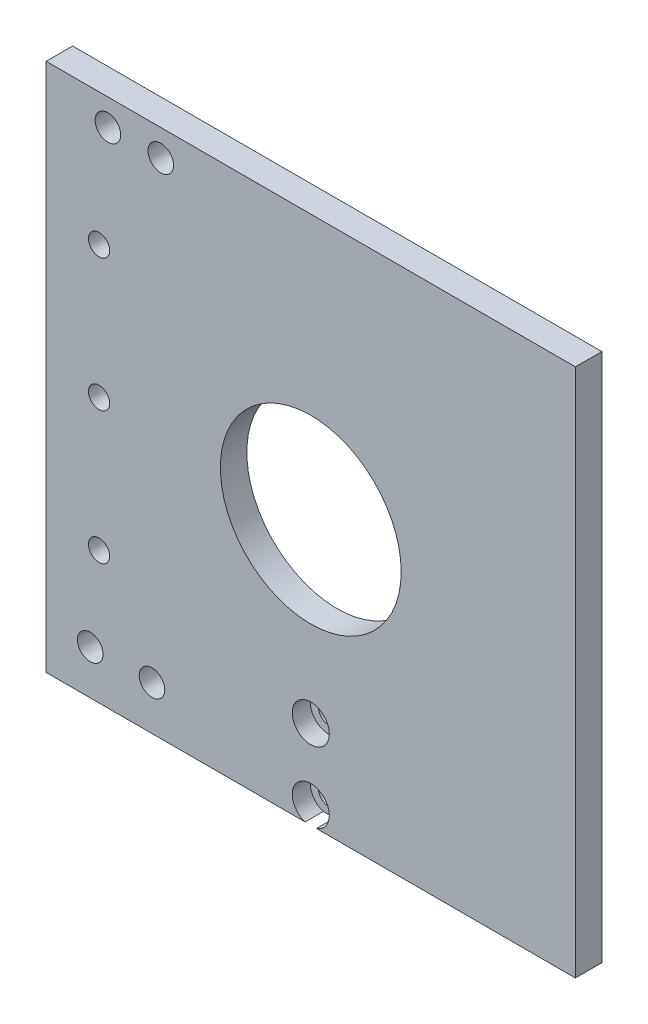
SolidWorks part; units mm, degrees
ref_plane "Front Plane" through (0, 0, 0) normal (0, 0, 1) x (1, 0, 0)
ref_plane "Top Plane" through (0, 0, 0) normal (0, 1, 0) x (1, 0, 0)
ref_plane "Right Plane" through (0, 0, 0) normal (1, 0, 0) x (0, 0, -1)
sketch "Sketch1" plane through (0, 0, 0) normal (0, 0, 1) x (1, 0, 0)
  line L1 (30, -30) -> (-30, -30)
  line L2 (30, -30) -> (30, 30)
  line L3 (30, 30) -> (-30, 30)
  line L4 (-30, -30) -> (-30, 30)
  line L5 (30, -30) -> (-30, 30) construction
  line L6 (30, 30) -> (-30, -30) construction
  point P0 (0, 0)
  dimension "D1" = 60
  dimension "D2" = 60
extrude "Boss-Extrude1" add sketch "Sketch1" along normal blind 3
sketch "Sketch2" plane through (0, 0, 3) normal (0, 0, 1) x (1, 0, 0)
  circle A0 centre (0, 0) radius 10.25
extrude "Cut-Extrude1" cut sketch "Sketch2" against normal through all
sketch "Sketch3" plane through (0, 0, 0) normal (0, 0, -1) x (-1, 0, 0)
  circle A0 centre (18, -25) radius 1.45
  circle A1 centre (25, -25) radius 1.45
extrude "Servo_Y_Mount_D2p9" cut sketch "Sketch3" against normal blind 3.01
sketch "Sketch4" plane through (0, 0, 0) normal (0, 0, -1) x (-1, 0, 0)
  circle A0 centre (17, 27) radius 1.45
  circle A1 centre (23, 27) radius 1.45
extrude "Cut-Extrude5" cut sketch "Sketch4" against normal through all
sketch "Sketch5" plane through (0, 0, 3) normal (0, 0, 1) x (1, 0, 0)
  circle A0 centre (-24, -15) radius 1.2
  circle A1 centre (-24, 0) radius 1.2
  circle A2 centre (-24, 15) radius 1.2
extrude "GuideRail1_D2p4" cut sketch "Sketch5" against normal blind 3.01
sketch "Sketch6" plane through (0, 0, 3) normal (0, 0, 1) x (1, 0, 0)
  circle A0 centre (0, -28) radius 1.2
  circle A1 centre (0, -20) radius 1.2
extrude "GuideBlock2_D2p4" cut sketch "Sketch6" against normal blind 3.01
sketch "Sketch7" plane through (0, 0, 3) normal (0, 0, 1) x (1, 0, 0)
  circle A0 centre (0, -28) radius 2.1
  circle A1 centre (0, -20) radius 2.1
extrude "GuideBlock2_HeadCounterbore_D4p2" cut sketch "Sketch7" against normal blind 2.05
